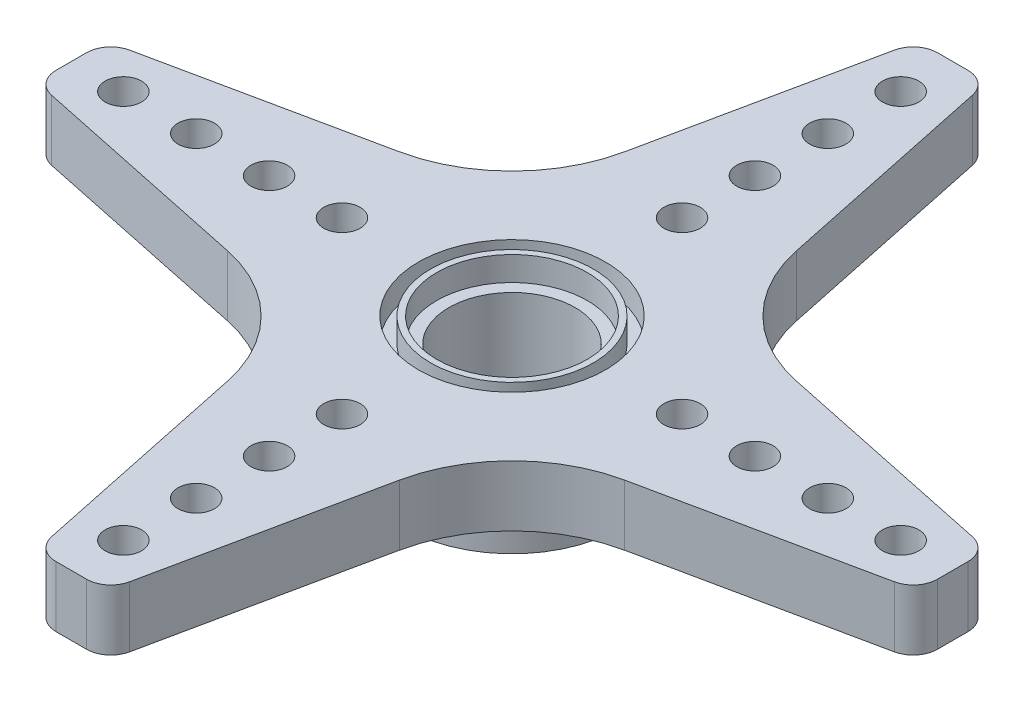
SolidWorks part; units mm, degrees
ref_plane "前视基准面" through (0, 0, 0) normal (0, 0, 1) x (1, 0, 0)
ref_plane "上视基准面" through (0, 0, 0) normal (0, 1, 0) x (1, 0, 0)
ref_plane "右视基准面" through (0, 0, 0) normal (1, 0, 0) x (0, 0, -1)
sketch "草图1" plane through (0, 0, 0) normal (0, 1, 0) x (1, 0, 0)
  circle A0 centre (0, 0) radius 4.5
  circle A1 centre (0, 0) radius 20
  circle A2 centre (0, 0) radius 2.6
extrude "凸台-拉伸1" add sketch "草图1" along normal blind 2.8 contours A0
sketch "草图2" plane through (0, 2.8, 0) normal (0, 1, 0) x (1, 0, 0)
  line L1 (0, 0) -> (0.65, 0)
  line L2 (0, 0) -> (0.65, 0)
  line L11 (-17.3485, 1.6068) -> (-8.1726, 3.5338)
  line L15 (1.6068, 17.3485) -> (3.5338, 8.1726)
  line L17 (-1.6068, 17.3485) -> (-3.5338, 8.1726)
  line L24 (0, 0) -> (0, -16.75)
  line L25 (-1.6068, -17.3485) -> (-3.5338, -8.1726)
  line L26 (1.6068, -17.3485) -> (3.5338, -8.1726)
  line L29 (0, 25) -> (1.44, 18.1429)
  line L30 (0, 25) -> (-1.44, 18.1429)
  line L31 (17.3485, -1.6068) -> (8.1726, -3.5338)
  line L32 (17.3485, 1.6068) -> (8.1726, 3.5338)
  line L33 (18.1429, -0.6282) -> (18.1429, 0.6282)
  line L34 (-0.6282, -18.1429) -> (0.6282, -18.1429)
  line L35 (-18.1429, 0.6282) -> (-18.1429, -0.6282)
  line L36 (0.6282, 18.1429) -> (-0.6282, 18.1429)
  line L37 (0, -18.1429) -> (0, -18.2)
  line L38 (2.6, 0) -> (-2.6, 0)
  line L42 (-17.3485, -1.6068) -> (-8.1726, -3.5338)
  line L43 (-25, 0) -> (-19.9721, 1.0559) [skipped]
  line L44 (-25, 0) -> (-19.9721, -1.0559) [skipped]
  circle A0 centre (0, 0) radius 18.2
  circle A13 centre (0, 0) radius 20
  circle A14 centre (-7, 0) radius 0.75
  circle A15 centre (-10, 0) radius 0.75
  circle A16 centre (-13, 0) radius 0.75
  circle A17 centre (-16, 0) radius 0.75
  circle A18 centre (0, 7) radius 0.75
  circle A19 centre (0, 10) radius 0.75
  circle A20 centre (0, 13) radius 0.75
  circle A21 centre (0, 16) radius 0.75
  circle A22 centre (7, 0) radius 0.75
  circle A23 centre (10, 0) radius 0.75
  circle A24 centre (13, 0) radius 0.75
  circle A25 centre (16, 0) radius 0.75
  circle A26 centre (0, -7) radius 0.75
  circle A27 centre (0, -10) radius 0.75
  circle A28 centre (0, -13) radius 0.75
  circle A29 centre (0, -16) radius 0.75
  arc A30 (8.1726, 3.5338) -> (3.5338, 8.1726) centre (9.4057, 9.4057) cw
  arc A31 (-3.5338, 8.1726) -> (-8.1726, 3.5338) centre (-9.4057, 9.4057) cw
  arc A32 (-8.1726, -3.5338) -> (-3.5338, -8.1726) centre (-9.4057, -9.4057) cw
  arc A33 (3.5338, -8.1726) -> (8.1726, -3.5338) centre (9.4057, -9.4057) cw
  arc A34 (18.1429, 0.6282) -> (17.3485, 1.6068) centre (17.1429, 0.6282) ccw
  arc A35 (17.3485, -1.6068) -> (18.1429, -0.6282) centre (17.1429, -0.6282) ccw
  arc A36 (-1.6068, -17.3485) -> (-0.6282, -18.1429) centre (-0.6282, -17.1429) ccw
  arc A37 (0.6282, -18.1429) -> (1.6068, -17.3485) centre (0.6282, -17.1429) ccw
  arc A38 (-17.3485, 1.6068) -> (-18.1429, 0.6282) centre (-17.1429, 0.6282) ccw
  arc A39 (-18.1429, -0.6282) -> (-17.3485, -1.6068) centre (-17.1429, -0.6282) ccw
  arc A40 (1.6068, 17.3485) -> (0.6282, 18.1429) centre (0.6282, 17.1429) ccw
  arc A41 (-0.6282, 18.1429) -> (-1.6068, 17.3485) centre (-0.6282, 17.1429) ccw
  circle A43 centre (0, 0) radius 2.6
  point P20 (0, 0)
  point P77 (0, 0)
  point P90 (0, 0)
  point P120 (0, 0)
  dimension "D4" = 7
  dimension "D8" = 6
  dimension "D9" = 1
  dimension "D7" = 4
  dimension "D5" = 4
  dimension "D6" = 4
  dimension "D10" = 4
extrude "凸台-拉伸4" add sketch "草图2" along normal blind 2.5
sketch "草图4" plane through (0, 5.3, 0) normal (0, 1, 0) x (1, 0, 0)
  circle A0 centre (0, 0) radius 3.1
  circle A1 centre (0, 0) radius 3.35
  circle A2 centre (0, 0) radius 3.85
  circle M41 centre (0, 0) radius 2.6
extrude "切除-拉伸1" cut sketch "草图4" against normal blind 1 contours A0 M41 | A2 A1
